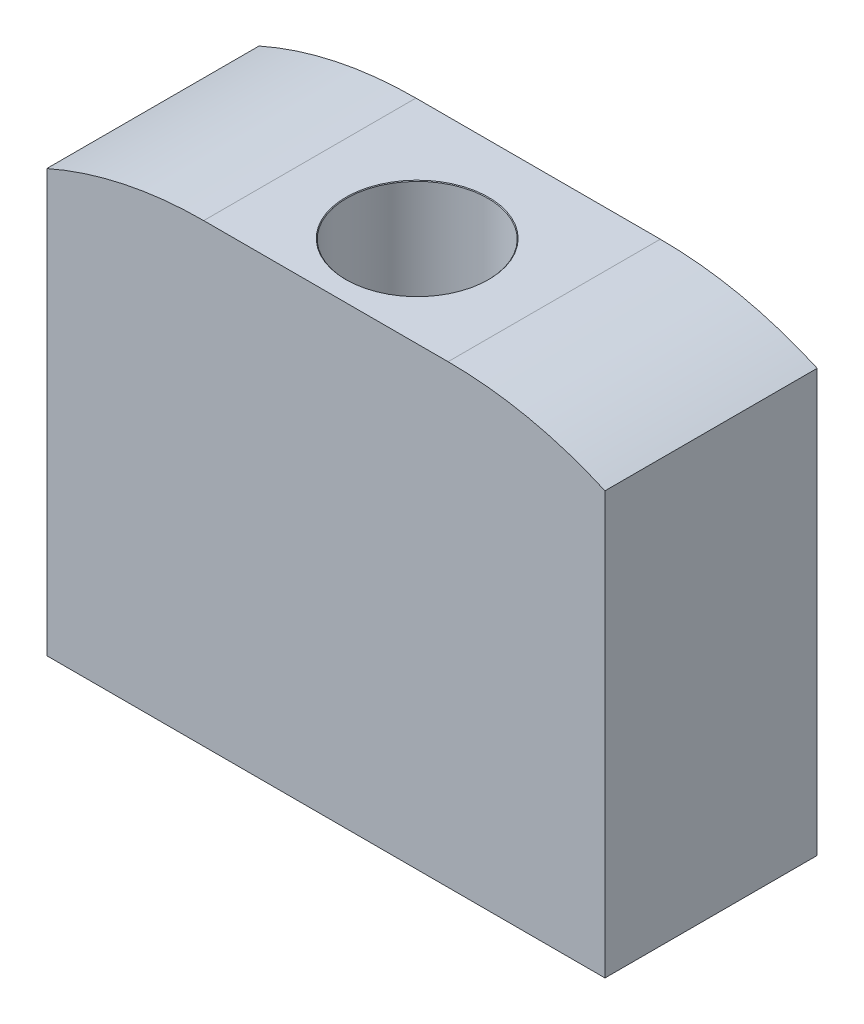
SolidWorks part; units mm, degrees
ref_plane "Front" through (0, 0, 0) normal (0, 0, 1) x (1, 0, 0)
ref_plane "Top" through (0, 0, 0) normal (0, 1, 0) x (1, 0, 0)
ref_plane "Right" through (0, 0, 0) normal (1, 0, 0) x (0, 0, -1)
sketch "Sketch1" plane through (0, 0, 0) normal (0, 0, 1) x (1, 0, 0)
  line L1 (-10.85, 0) -> (10.85, 0)
  line L2 (-10.85, 0) -> (-10.85, 17.7)
  line L3 (-10.85, 17.7) -> (10.85, 17.7)
  line L4 (10.85, 0) -> (10.85, 17.7)
  dimension "D1" = 21.7
  dimension "D2" = 17.7
extrude "Boss-Extrude1" add sketch "Sketch1" along normal mid plane 8.25
sketch "Sketch3" plane through (0, 0, 4.125) normal (0, 0, 1) x (1, 0, 0)
  line L0 (-4.75, 2.7) -> (4.75, 2.7) construction
  line L1 (-4.75, 17.7) -> (4.75, 17.7)
  line L2 (-4.75, -12.3) -> (4.75, -12.3)
  line L3 (0, 2.7) -> (0, 0) construction
  line L4 (10.85, 17.7) -> (-10.85, 17.7) construction
  arc A0 (-4.75, 17.7) -> (-4.75, -12.3) centre (-4.75, 2.7) ccw
  arc A1 (4.75, -12.3) -> (4.75, 17.7) centre (4.75, 2.7) ccw
  point P2 (0, 2.7)
  point P10 (4.9203, -12.5143)
  point P11 (5, 1.8321)
  dimension "D2" = 15
  dimension "D1" = 9.5
extrude "Cut-Extrude1" cut sketch "Sketch3" against normal up to next (8.25 mm away) flip side to cut
hole_wizard "CBORE for M2.5 SHCS1" positions "Sketch4" profile "Sketch5" counterbore size "M2.5" standard "ANSI Metric" end condition up to next
sketch "Sketch4" plane through (0, 17.7, 0) normal (0, 1, 0) x (1, 0, 0)
  line L0 (4.75, 4.125) -> (-4.75, 4.125) construction
  line L2 (0, -0.575) -> (0, 4.125) construction
  point P0 (0, -0.575)
  dimension "D1" = 4.7
sketch "Sketch5" plane through (0, 17.7, 0.575) normal (1, 0, 0) x (0, 0, 1)
  line L0 (0, 0) -> (0, 17.7)
  line L1 (0, 17.7) -> (1.45, 17.7)
  line L3 (1.45, 17.7) -> (1.45, 12.5)
  line L4 (2.75, 12.5) -> (1.45, 12.5)
  line L5 (2.75, 12.5) -> (2.75, 0.025)
  line L6 (2.75, 0.025) -> (2.775, 0)
  line L7 (2.775, 0) -> (0, 0)
  line L8 (-2.75, 0.025) -> (-2.775, 0) construction
  line L11 (0, -6.35) -> (0, 107.95) construction
  dimension "Thru Hole Dia." = 2.9
  dimension "Thru Hole Depth" = 17.7
  dimension "C'Bore Dia." = 5.5
  dimension "C'Bore Depth" = 12.5
  dimension "Near C'Sink Dia." = 5.55
  dimension "Near C'Sink Angle" = 90
